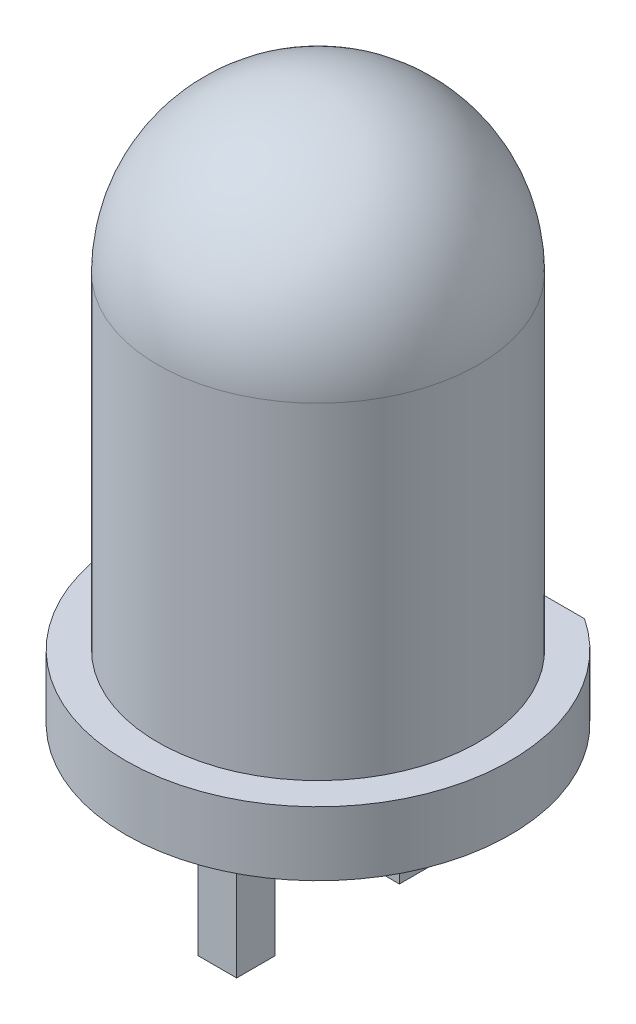
SolidWorks part; units mm, degrees
ref_plane "Frontal" through (0, 0, 0) normal (0, 0, 1) x (1, 0, 0)
ref_plane "Superior" through (0, 0, 0) normal (0, 1, 0) x (1, 0, 0)
ref_plane "Direito" through (0, 0, 0) normal (1, 0, 0) x (0, 0, -1)
sketch "Esboço1" plane through (0, 0, 0) normal (1, 0, 0) x (0, 0, -1)
  line L0 (0, 0) -> (0, 8.6)
  line L1 (0, 0) -> (3, 0)
  line L2 (3, 0) -> (3, 1)
  line L3 (2.5, 6.1) -> (2.5, 1)
  line L4 (2.5, 1) -> (3, 1)
  arc A0 (2.5, 6.1) -> (0, 8.6) centre (0, 6.1) ccw
  point P5 (0, 8.6)
  dimension "D2" = 5
  dimension "D1" = 8.6
revolve "Revolução1" add sketch "Esboço1" angle 360 about L0
sketch "Esboço4" plane through (0, 0, 0) normal (0, 1, 0) x (1, 0, 0)
  line L0 (-3.6263, 2.5) -> (3.6263, 2.5)
  line L1 (3.6263, 2.5) -> (3.6263, 3.251)
  line L2 (3.6263, 3.251) -> (-3.6263, 3.251)
  line L3 (0, 3.251) -> (0, 2.5) construction
  line L4 (-3.6263, 2.5) -> (-3.6263, 3.251)
  circle A0 centre (0, 0) radius 2.5 construction
extrude "Corte-extrusão1" cut sketch "Esboço4" along normal up to surface (1 mm away) up to face at (0, 1, -2.5)
sketch "Esboço5" plane through (0, 0, 0) normal (0, -1, 0) x (1, 0, 0)
  line L0 (0, -1.27) -> (0, 1.27) construction
  line L1 (0, 0) -> (1.3728, 0) construction
  line L2 (-0.3, 1.57) -> (0.3, 1.57)
  line L3 (-0.3, 1.57) -> (-0.3, 0.97)
  line L4 (-0.3, 0.97) -> (0.3, 0.97)
  line L5 (0.3, 1.57) -> (0.3, 0.97)
  line L6 (-0.3, 1.57) -> (0.3, 0.97) construction
  line L7 (-0.3, 0.97) -> (0.3, 1.57) construction
  line L8 (-0.3, -0.97) -> (0.3, -1.57) construction
  line L9 (-0.3, -1.57) -> (0.3, -0.97) construction
  line L10 (0.3, -1.57) -> (0.3, -0.97)
  line L11 (-0.3, -0.97) -> (0.3, -0.97)
  line L12 (-0.3, -1.57) -> (-0.3, -0.97)
  line L13 (-0.3, -1.57) -> (0.3, -1.57)
  circle A0 centre (0, 0) radius 3 construction
  dimension "D1" = 1.27
extrude "Ressalto-extrusão1" add sketch "Esboço5" along normal blind 27
sketch "Esboço6" plane through (0, -27, 0) normal (0, -1, 0) x (1, 0, 0)
  line L4 (-0.3, -0.97) -> (-0.3, -1.57)
  line L5 (-0.3, -1.57) -> (0.3, -1.57)
  line L6 (0.3, -1.57) -> (0.3, -0.97)
  line L7 (0.3, -0.97) -> (-0.3, -0.97)
  line L8 (-0.3, -0.97) -> (-0.3, -1.57)
  line L9 (-0.3, -1.57) -> (0.3, -1.57)
  line L10 (0.3, -1.57) -> (0.3, -0.97)
  line L11 (0.3, -0.97) -> (-0.3, -0.97)
  dimension "D1" = 0
extrude "Corte-extrusão2" cut sketch "Esboço6" against normal blind 1.5
sketch "Esboço27" plane through (0, -27, 0) normal (0, -1, 0) x (1, 0, 0)
  circle A0 centre (0, 0) radius 4.6247
extrude "Corte-extrusão3" cut sketch "Esboço27" against normal blind 24.5
